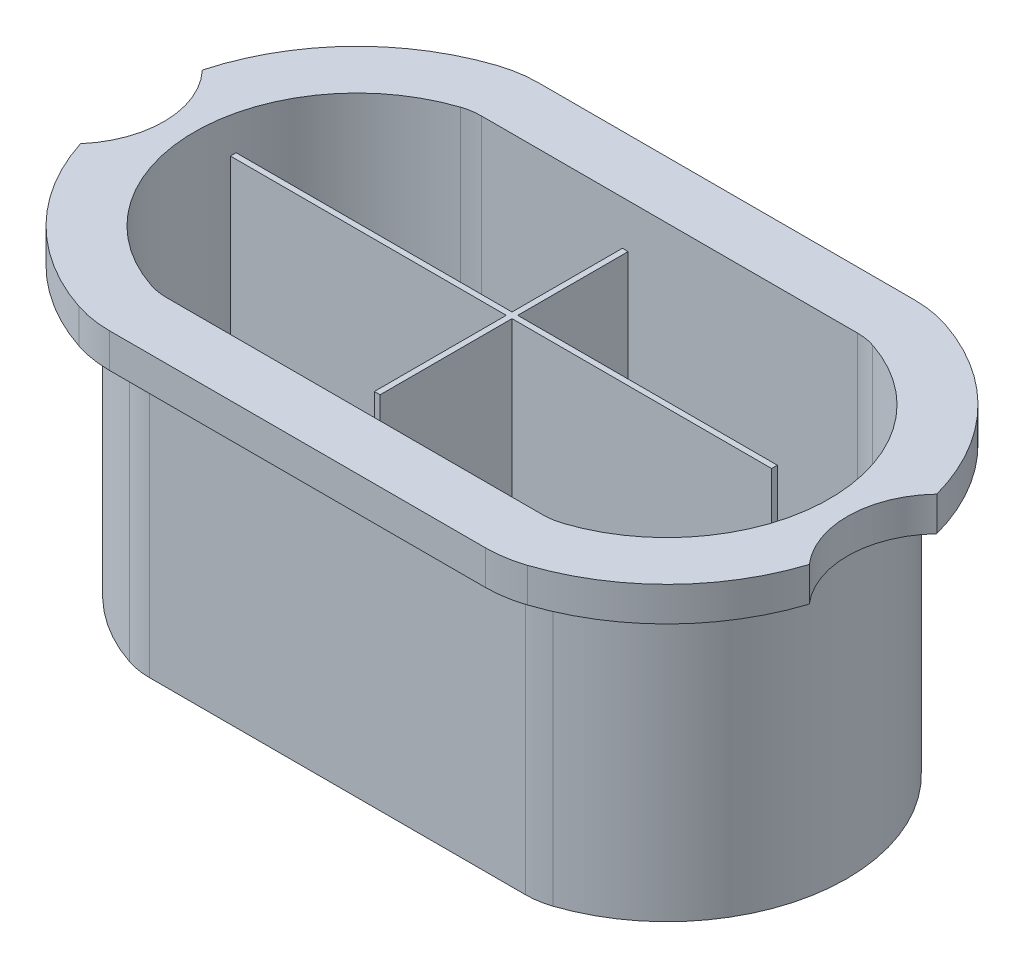
SolidWorks part; units mm, degrees
ref_plane "Front Plane" through (0, 0, 0) normal (0, 0, 1) x (1, 0, 0)
ref_plane "Top Plane" through (0, 0, 0) normal (0, 1, 0) x (1, 0, 0)
ref_plane "Right Plane" through (0, 0, 0) normal (1, 0, 0) x (0, 0, -1)
sketch "Sketch1" plane through (0, 0, 0) normal (0, 1, 0) x (1, 0, 0)
  line L4 (34.5405, 38.6091) -> (-36.4595, 38.6091)
  line L6 (34.5405, -36.3909) -> (-36.4595, -36.3909)
  arc A0 (-36.4595, 38.6091) -> (-36.4595, -36.3909) centre (-28.022, 1.1091) ccw
  arc A1 (34.5405, 38.6091) -> (34.5405, -36.3909) centre (26.103, 1.1091) cw
  point P11 (0.5405, 0.9091)
extrude "Boss-Extrude1" add sketch "Sketch1" along normal blind 6
fillet "Fillet1" radius 20 4 edges at (34.5405, 3, 36.3909) (34.5405, 3, -38.6091) (-36.4595, 3, -38.6091) (-36.4595, 3, 36.3909)
sketch "Sketch3" plane through (0, 0, 0) normal (0, -1, 0) x (1, 0, 0)
  line L4 (31.9074, 29.3909) -> (-33.8264, 29.3909)
  line L5 (-33.8264, -31.6091) -> (31.9074, -31.6091)
  line L6 (31.9074, 29.3909) -> (-33.8264, 29.3909)
  line L7 (-33.8264, -31.6091) -> (31.9074, -31.6091)
  arc A4 (36.0001, -30.9481) -> (36.0001, 28.7299) centre (26.103, -1.1091) ccw
  arc A5 (36.0001, -30.9481) -> (36.0001, 28.7299) centre (26.103, -1.1091) ccw
  arc A6 (-37.919, 28.7299) -> (-37.919, -30.9481) centre (-28.022, -1.1091) ccw
  arc A7 (-37.919, 28.7299) -> (-37.919, -30.9481) centre (-28.022, -1.1091) ccw
  arc A10 (-37.919, -30.9481) -> (-33.8264, -31.6091) centre (-33.8264, -18.6091) ccw
  arc A11 (-37.919, -30.9481) -> (-33.8264, -31.6091) centre (-33.8264, -18.6091) ccw
  arc A12 (36.0001, 28.7299) -> (31.9074, 29.3909) centre (31.9074, 16.3909) ccw
  arc A13 (36.0001, 28.7299) -> (31.9074, 29.3909) centre (31.9074, 16.3909) ccw
  arc A14 (31.9074, -31.6091) -> (36.0001, -30.9481) centre (31.9074, -18.6091) ccw
  arc A15 (-33.8264, 29.3909) -> (-37.919, 28.7299) centre (-33.8264, 16.3909) ccw
  arc A16 (31.9074, -31.6091) -> (36.0001, -30.9481) centre (31.9074, -18.6091) ccw
  arc A17 (-33.8264, 29.3909) -> (-37.919, 28.7299) centre (-33.8264, 16.3909) ccw
  dimension "D1" = 7
ref_plane "Plane1" through (31.9074, 0, -31.6091) normal (1, 0, 0) x (0, 0, -1)
sketch "Sketch4" plane through (31.9074, 0, -31.6091) normal (1, 0, 0) x (0, 0, -1)
  line L1 (0, 0) -> (-3, 0)
  line L2 (0, 0) -> (0, -50)
  line L3 (0, -50) -> (-3, -50)
  line L4 (-3, 0) -> (-3, -50)
sweep "Sweep1" add profiles "Sketch4" path "Sketch3"
sketch "Sketch6" plane through (0, 0, 0) normal (0, 1, 0) x (1, 0, 0)
  circle A0 centre (75, 0) radius 16.2457
  circle A1 centre (-76.919, 0) radius 16.2457
extrude "Cut-Extrude1" cut sketch "Sketch6" along normal blind 10
sketch "Sketch7" plane through (0, -50, 0) normal (0, -1, 0) x (1, 0, 0)
  line L11 (31.9074, 26.3909) -> (-33.8264, 26.3909)
  line L12 (-33.8264, -28.6091) -> (31.9074, -28.6091)
  line L13 (31.9074, 26.3909) -> (-33.8264, 26.3909)
  line L14 (-33.8264, -28.6091) -> (31.9074, -28.6091)
  arc A33 (35.0556, 25.8824) -> (31.9074, 26.3909) centre (31.9074, 16.3909) ccw
  arc A34 (-33.8264, 26.3909) -> (-36.9746, 25.8824) centre (-33.8264, 16.3909) ccw
  arc A35 (-36.9746, 25.8824) -> (-36.9746, -28.1007) centre (-28.022, -1.1091) ccw
  arc A36 (-36.9746, -28.1007) -> (-33.8264, -28.6091) centre (-33.8264, -18.6091) ccw
  arc A37 (31.9074, -28.6091) -> (35.0556, -28.1007) centre (31.9074, -18.6091) ccw
  arc A38 (35.0556, -28.1007) -> (35.0556, 25.8824) centre (26.103, -1.1091) ccw
  arc A39 (35.0556, 25.8824) -> (31.9074, 26.3909) centre (31.9074, 16.3909) ccw
  arc A40 (-33.8264, 26.3909) -> (-36.9746, 25.8824) centre (-33.8264, 16.3909) ccw
  arc A41 (-36.9746, 25.8824) -> (-36.9746, -28.1007) centre (-28.022, -1.1091) ccw
  arc A42 (-36.9746, -28.1007) -> (-33.8264, -28.6091) centre (-33.8264, -18.6091) ccw
  arc A43 (31.9074, -28.6091) -> (35.0556, -28.1007) centre (31.9074, -18.6091) ccw
  arc A44 (35.0556, -28.1007) -> (35.0556, 25.8824) centre (26.103, -1.1091) ccw
  dimension "D1" = 0
extrude "Boss-Extrude2" add sketch "Sketch7" against normal blind 3
sketch "Sketch9" plane through (0, 0, 0) normal (0, -1, 0) x (1, 0, 0)
  line L10 (-33.8264, -28.6091) -> (31.9074, -28.6091)
  line L11 (31.9074, 26.3909) -> (-33.8264, 26.3909)
  line L12 (-33.8264, -28.6091) -> (31.9074, -28.6091)
  line L13 (31.9074, 26.3909) -> (-33.8264, 26.3909)
  arc A34 (31.9074, -28.6091) -> (35.0556, -28.1007) centre (31.9074, -18.6091) ccw
  arc A35 (-36.9746, -28.1007) -> (-33.8264, -28.6091) centre (-33.8264, -18.6091) ccw
  arc A36 (-36.9746, 25.8824) -> (-36.9746, -28.1007) centre (-28.022, -1.1091) ccw
  arc A37 (-33.8264, 26.3909) -> (-36.9746, 25.8824) centre (-33.8264, 16.3909) ccw
  arc A38 (35.0556, 25.8824) -> (31.9074, 26.3909) centre (31.9074, 16.3909) ccw
  arc A39 (35.0556, -28.1007) -> (35.0556, 25.8824) centre (26.103, -1.1091) ccw
  arc A40 (31.9074, -28.6091) -> (35.0556, -28.1007) centre (31.9074, -18.6091) ccw
  arc A41 (-36.9746, -28.1007) -> (-33.8264, -28.6091) centre (-33.8264, -18.6091) ccw
  arc A42 (-36.9746, 25.8824) -> (-36.9746, -28.1007) centre (-28.022, -1.1091) ccw
  arc A43 (-33.8264, 26.3909) -> (-36.9746, 25.8824) centre (-33.8264, 16.3909) ccw
  arc A44 (35.0556, 25.8824) -> (31.9074, 26.3909) centre (31.9074, 16.3909) ccw
  arc A45 (35.0556, -28.1007) -> (35.0556, 25.8824) centre (26.103, -1.1091) ccw
  dimension "D1" = 3
extrude "Cut-Extrude2" cut sketch "Sketch9" against normal blind 44
sketch "Sketch10" plane through (0, -47, 0) normal (0, 1, 0) x (1, 0, 0)
  line L2 (-0.4595, 1.6091) -> (44.9059, 1.6091)
  line L5 (-1.4595, 1.6091) -> (-1.4595, 20.9005)
  line L7 (-1.4595, -22.4355) -> (-0.4595, -22.4355)
  line L8 (-0.4595, 0.6091) -> (44.9059, 0.6091)
  line L9 (-0.4595, -22.4355) -> (-0.4595, 0.6091)
  line L11 (-1.4595, -22.4355) -> (-1.4595, 0.6091)
  line L12 (-49.6632, 0.6091) -> (-1.4595, 0.6091)
  line L14 (-49.6632, 1.6091) -> (-1.4595, 1.6091)
  line L17 (-0.4595, 20.9005) -> (-1.4595, 20.9005)
  line L18 (-49.6632, 0.6091) -> (-49.6632, 1.6091)
  line L19 (44.9059, 0.6091) -> (44.9059, 1.6091)
  line L20 (-0.4595, 1.6091) -> (-0.4595, 20.9005)
extrude "Boss-Extrude3" add sketch "Sketch10" along normal up to surface (53 mm away) up to face at (-0.9595, 6, -1.1091)
